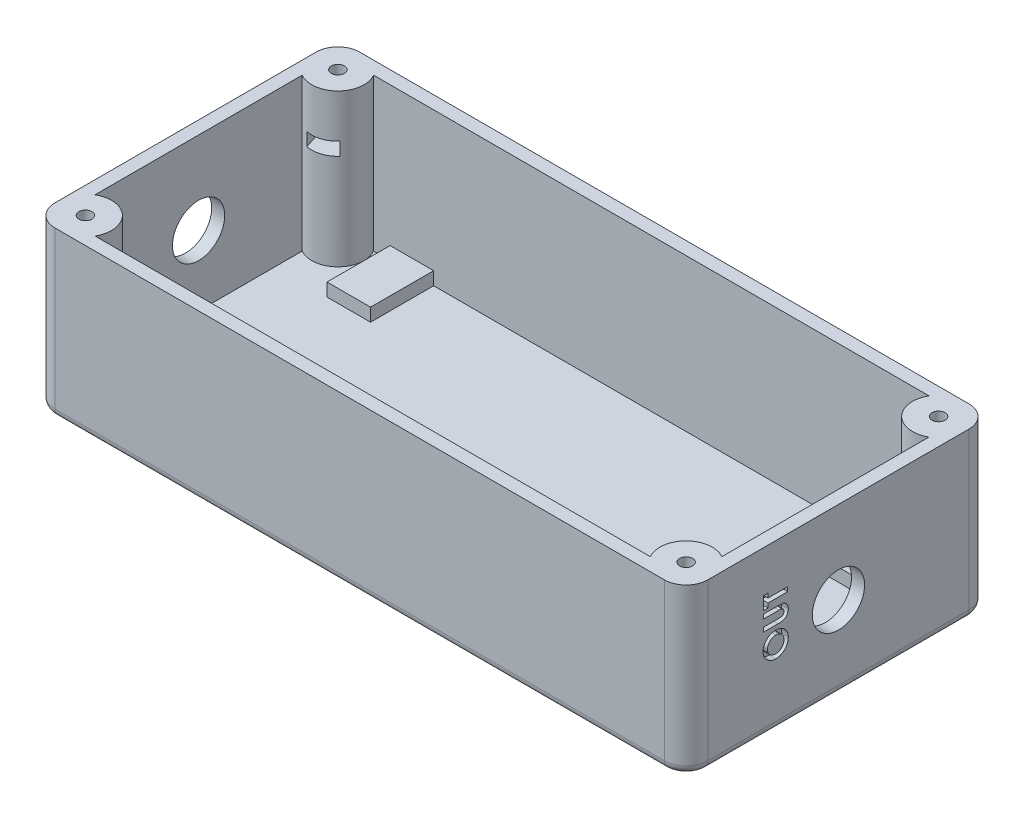
SolidWorks part; units mm, degrees
ref_plane "Спереди" through (0, 0, 0) normal (0, 0, 1) x (1, 0, 0)
ref_plane "Сверху" through (0, 0, 0) normal (0, 1, 0) x (1, 0, 0)
ref_plane "Справа" through (0, 0, 0) normal (1, 0, 0) x (0, 0, -1)
sketch "Эскиз1" plane through (0, 0, 0) normal (0, 1, 0) x (1, 0, 0)
  line L0 (-1000, 0) -> (49000, 0) construction
  line L1 (-1000, -35) -> (49000, -35) construction
  line L2 (-1000, 35) -> (49000, 35) construction
  line L3 (0, -1000) -> (0, 49000) construction
  line L4 (75, -1000) -> (75, 49000) construction
  line L5 (-75, -1000) -> (-75, 49000) construction
  line L6 (-75, 35) -> (-75, -35)
  line L7 (-75, -35) -> (75, -35)
  line L8 (75, -35) -> (75, 35)
  line L9 (75, 35) -> (-75, 35)
extrude "Бобышка-Вытянуть1" add sketch "Эскиз1" along normal blind 3
sketch "Эскиз2" plane through (0, 3, 0) normal (0, 1, 0) x (1, 0, 0)
  line L1 (75, -35) -> (-75, -35)
  line L2 (75, -35) -> (75, 35)
  line L3 (75, 35) -> (-75, 35)
  line L4 (-75, -35) -> (-75, 35)
  line L5 (75, -35) -> (-75, 35) construction
  line L6 (75, 35) -> (-75, -35) construction
  line L10 (72, 32) -> (-72, 32)
  line L11 (-72, -32) -> (-72, 32)
  line L12 (72, -32) -> (-72, -32)
  line L13 (72, -32) -> (72, 32)
  point P0 (0, 0)
  dimension "D2" = 3
extrude "Бобышка-Вытянуть2" add sketch "Эскиз2" along normal blind 35
sketch "Эскиз3" plane through (0, 3, 0) normal (0, 1, 0) x (1, 0, 0)
  line L0 (-1000, 0) -> (49000, 0) construction
  line L1 (0, -1000) -> (0, 49000) construction
  line L2 (60, -1000) -> (60, 49000) construction
  line L3 (-60, -1000) -> (-60, 49000) construction
  line L4 (-1000, -27.5) -> (49000, -27.5) construction
  line L5 (-1000, 27.5) -> (49000, 27.5) construction
  line L6 (52, -1000) -> (52, 49000) construction
  line L7 (-1000, 19.5) -> (49000, 19.5) construction
  line L8 (-60, 34.2211) -> (-60, 17.5)
  line L9 (-60, 17.5) -> (-50, 17.5)
  line L10 (-50, 17.5) -> (-50, 34.2211)
  line L11 (-50, 34.2211) -> (-60, 34.2211)
  line L12 (52, 19.5) -> (60, 19.5)
  line L13 (-50, -17.5) -> (-60, -17.5)
  line L14 (-60, -17.5) -> (-60, -33.9396)
  line L15 (-60, -33.9396) -> (-50, -33.9396)
  line L16 (-50, -33.9396) -> (-50, -17.5)
  line L17 (60, 19.5) -> (60, 34.2211)
  line L18 (60, 34.2211) -> (52, 34.2211)
  line L19 (52, 34.2211) -> (52, 19.5)
  line L20 (-1000, -13.5) -> (49000, -13.5) construction
  line L21 (52, -13.5) -> (52, -33.9396)
  line L22 (52, -33.9396) -> (60, -33.9396)
  line L23 (60, -33.9396) -> (60, -13.5)
  line L24 (60, -13.5) -> (52, -13.5)
  dimension "D1" = 8
  dimension "D2" = 14
extrude "Бобышка-Вытянуть3" add sketch "Эскиз3" along normal blind 3
sketch "Эскиз4" plane through (0, 3, 0) normal (0, 1, 0) x (1, 0, 0)
  circle A0 centre (-68.9962, 28.9962) radius 6.0038
  circle A1 centre (-68.9973, -28.9973) radius 6.0027
  circle A2 centre (69.0019, 29.0019) radius 5.9981
  circle A3 centre (68.9966, -28.9966) radius 6.0034
extrude "Бобышка-Вытянуть4" add sketch "Эскиз4" along normal blind 35
ref_plane "Плоскость4" through (0, 28, 0) normal (0, 1, 0) x (1, 0, 0)
sketch "Эскиз5" plane through (0, 28, 0) normal (0, 1, 0) x (1, 0, 0)
  line L0 (-71.3158, 26.4233) -> (-69.4993, 20.8202)
  line L3 (-65.6082, 28.2737) -> (-66.6765, 31.569)
  line L4 (-66.6765, 31.569) -> (-70.0645, 32.2914)
  line L5 (-70.0645, 32.2914) -> (-72.3841, 29.7186)
  line L6 (-72.3841, 29.7186) -> (-71.3158, 26.4233)
  line L7 (-69.4663, -25.5651) -> (-72.2041, -27.6873)
  line L8 (-72.2041, -27.6873) -> (-71.7351, -31.1195)
  line L9 (-71.7351, -31.1195) -> (-68.5283, -32.4295)
  line L10 (-68.5283, -32.4295) -> (-65.7904, -30.3072)
  line L14 (70.1702, 25.7407) -> (72.4103, 28.3831)
  line L15 (72.4103, 28.3831) -> (71.242, 31.6442)
  line L16 (71.242, 31.6442) -> (67.8336, 32.2631)
  line L17 (67.8336, 32.2631) -> (65.5935, 29.6207)
  line L20 (65.8087, -30.3521) -> (68.5765, -32.4352)
  line L21 (68.5765, -32.4352) -> (71.7644, -31.0798)
  line L22 (71.7644, -31.0798) -> (72.1846, -27.6412)
  line L23 (72.1846, -27.6412) -> (69.4168, -25.5581)
  line L25 (-65.6082, 28.2737) -> (-63.546, 21.9127)
  line L26 (-63.546, 21.9127) -> (-69.1211, 20.1053)
  line L27 (-69.1211, 20.1053) -> (-69.4993, 20.8202)
  line L28 (-69.4663, -25.5651) -> (-64.9418, -22.0579)
  line L29 (-71.3158, 26.4233) -> (-67.9278, 25.7009) [skipped]
  line L30 (-67.9278, 25.7009) -> (-65.6082, 28.2737) [skipped]
  line L31 (-64.9418, -22.0579) -> (-61.2659, -26.8)
  line L32 (-65.7904, -30.3072) -> (-61.2659, -26.8)
  line L33 (69.4168, -25.5581) -> (64.4231, -21.7997)
  line L34 (-65.7904, -30.3072) -> (-66.2594, -26.875) [skipped]
  line L35 (-66.2594, -26.875) -> (-69.4663, -25.5651) [skipped]
  line L36 (65.8087, -30.3521) -> (60.2731, -26.1858)
  line L37 (60.2731, -26.1858) -> (63.8459, -21.4388)
  line L38 (63.8459, -21.4388) -> (64.4231, -21.7997)
  line L39 (65.5935, 29.6207) -> (61.7032, 25.0318)
  line L40 (69.4168, -25.5581) -> (66.2289, -26.9135) [skipped]
  line L41 (66.2289, -26.9135) -> (65.8087, -30.3521) [skipped]
  line L42 (70.1702, 25.7407) -> (65.9987, 20.8202)
  line L43 (65.9987, 20.8202) -> (61.279, 24.8215)
  line L44 (61.279, 24.8215) -> (61.7032, 25.0318)
  line L46 (65.5935, 29.6207) -> (66.7618, 26.3596) [skipped]
  line L47 (66.7618, 26.3596) -> (70.1702, 25.7407) [skipped]
  circle A0 centre (-68.9962, 28.9962) radius 3 construction
  circle A1 centre (-68.9973, -28.9973) radius 3 construction
  circle A2 centre (69.0019, 29.0019) radius 3 construction
  circle A3 centre (68.9966, -28.9966) radius 3 construction
extrude "Вырез-Вытянуть1" cut sketch "Эскиз5" against normal blind 3
sketch "Эскиз6" plane through (0, 38, 0) normal (0, 1, 0) x (1, 0, 0)
  circle A0 centre (-68.9962, 28.9962) radius 1.5
  circle A1 centre (69.0019, 29.0019) radius 1.5
  circle A2 centre (68.9966, -28.9966) radius 1.5
  circle A3 centre (-68.9973, -28.9973) radius 1.5
extrude "Вырез-Вытянуть2" cut sketch "Эскиз6" against normal blind 19
fillet "Скругление1" radius 5 4 edges at (75, 19, -35) (75, 19, 35) (-75, 19, -35) (-75, 19, 35)
fillet "Скругление2" radius 2 8 edges at (-73.5355, 0, -33.5355) (0, 0, -35) (73.5355, 0, -33.5355) (75, 0, 0) (73.5355, 0, 33.5355) (0, 0, 35) (-73.5355, 0, 33.5355) (-75, 0, 0)
sketch "Эскиз7" plane through (-75, 0, 0) normal (-1, 0, 0) x (0, 0, 1)
  line L0 (0, -1000) -> (0, 49000) construction
  line L1 (30, 0) -> (-30, 0) construction
  line L2 (-1035, 38) -> (48965, 38) construction
  line L3 (-1035, 19) -> (48965, 19) construction
  circle A0 centre (0, 19) radius 6
  point P5 (0, 0)
extrude "Вырез-Вытянуть3" cut sketch "Эскиз7" against normal blind 19
sketch "Эскиз8" plane through (75, 0, 0) normal (1, 0, 0) x (0, 0, -1)
  line L0 (0, -1000) -> (0, 49000) construction
  line L1 (30, 0) -> (-30, 0) construction
  line L2 (-1044.9571, 19) -> (48955.0429, 19) construction
  circle A0 centre (0, 19) radius 6
  point P5 (0, 0)
extrude "Вырез-Вытянуть4" cut sketch "Эскиз8" against normal blind 19
sketch "Эскиз9" plane through (-75, 0, 0) normal (-1, 0, 0) x (0, 0, 1)
  text T0 "<b>220 V</b>" font "Century Gothic" height 5.5
  point P3 (-12.6366, 28.9335)
  point P4 (0, 0)
  point P5 (0, 0)
  point P6 (-12.6366, 30.7155)
extrude "Вырез-Вытянуть5" cut sketch "Эскиз9" against normal blind 1.5
sketch "Эскиз10" plane through (75, 0, 0) normal (1, 0, 0) x (0, 0, -1)
  text T0 "<b>OUT</b>" font "Century Gothic" height 5.5
  point P3 (-12.5556, 22.6047)
  point P4 (-10.5305, 30.9481)
  point P5 (-11.7456, 26.5739)
  point P6 (0, 0)
  point P7 (0, 0)
  point P8 (-11.6646, 28.518)
extrude "Вырез-Вытянуть6" cut sketch "Эскиз10" against normal blind 1.5
